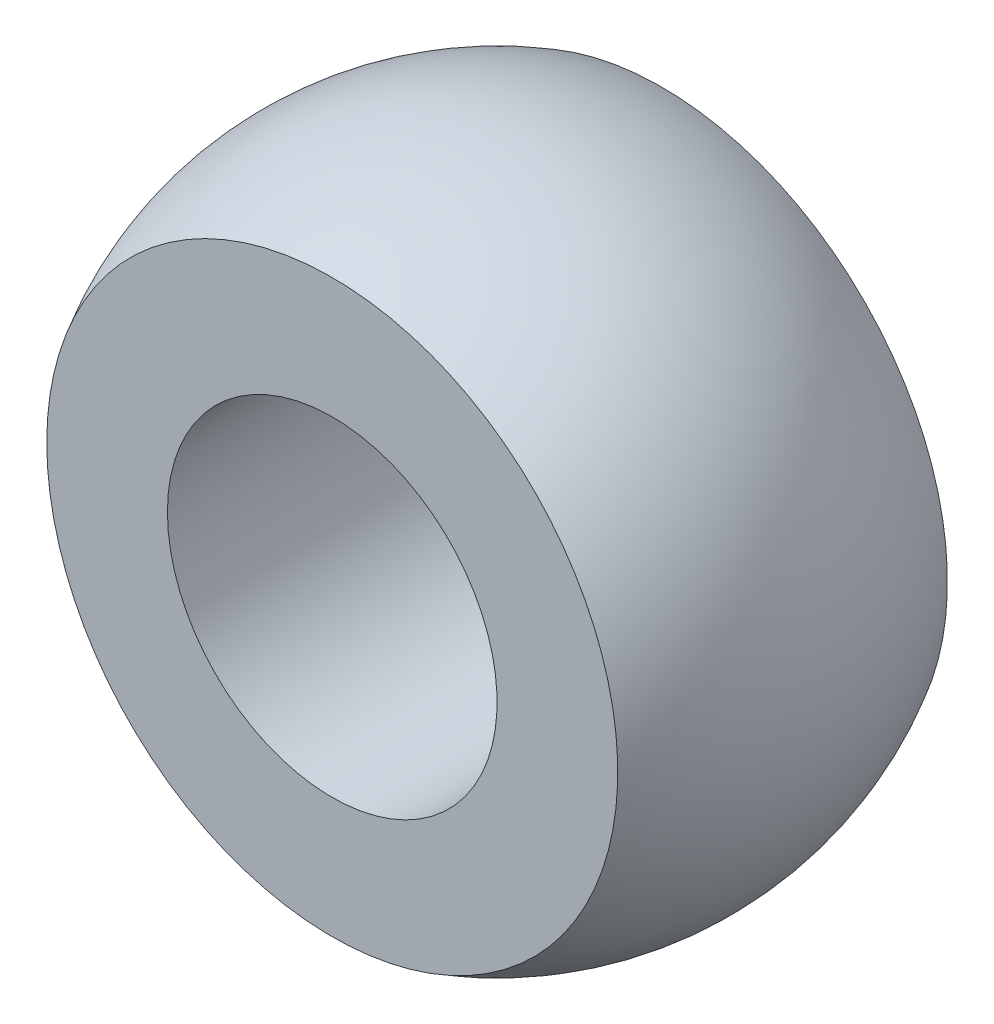
SolidWorks part; units mm, degrees
ref_plane "Front Plane" through (0, 0, 0) normal (0, 0, 1) x (1, 0, 0)
ref_plane "Top Plane" through (0, 0, 0) normal (0, 1, 0) x (1, 0, 0)
ref_plane "Right Plane" through (0, 0, 0) normal (1, 0, 0) x (0, 0, -1)
sketch "Sketch1" plane through (0, 0, 0) normal (0, 1, 0) x (1, 0, 0)
  line L0 (0, 3) -> (0, -3)
  line L1 (0, 3) -> (-5.1962, 3)
  line L2 (0, 0) -> (2.8154, 0) construction
  line L3 (0, -3) -> (-5.1962, -3)
  arc A0 (-5.1962, 3) -> (-5.1962, -3) centre (0, 0) ccw
  point P6 (0, 0)
  point P9 (-2.5981, 3)
  dimension "D1" = 12
revolve "Revolve1" add sketch "Sketch1" angle 360 about L0
sketch "Sketch2" plane through (0, 0, -3) normal (0, 0, -1) x (-1, 0, 0)
  circle A0 centre (0, 0) radius 3
  dimension "D1" = 6
extrude "Cut-Extrude1" cut sketch "Sketch2" against normal through all
